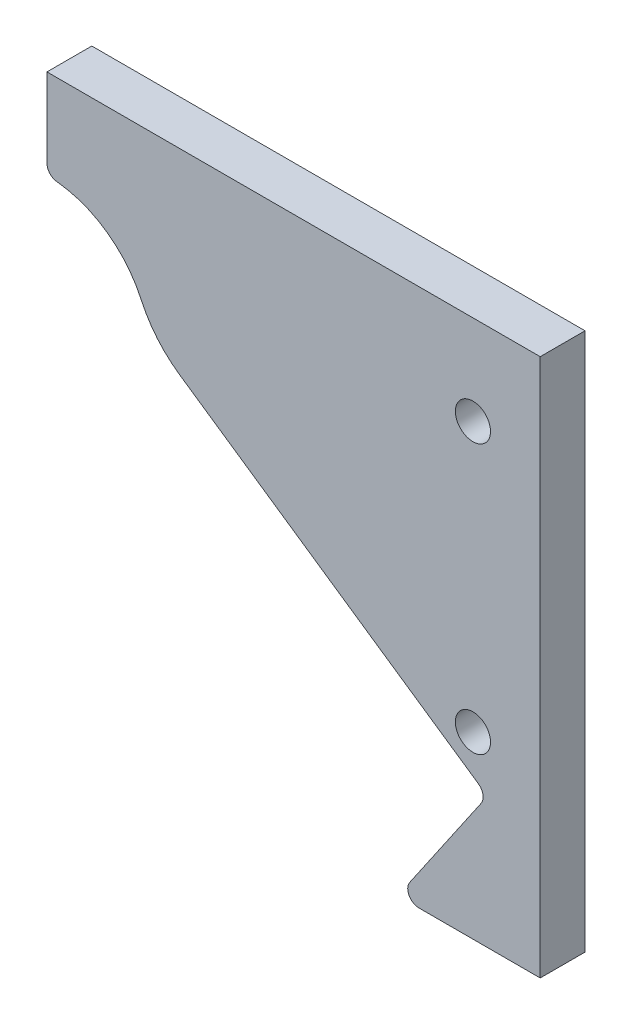
SolidWorks part; units mm, degrees
material "6061 Alloy"
ref_plane "X-Y Datum" through (0, 0, 0) normal (0, 0, 1) x (1, 0, 0)
ref_plane "X-Z Datum" through (0, 0, 0) normal (0, 1, 0) x (1, 0, 0)
ref_plane "Y-Z Datum" through (0, 0, 0) normal (1, 0, 0) x (0, 0, -1)
sketch "Sketch1" plane through (0, 0, 0) normal (0, 0, 1) x (1, 0, 0)
  line L0 (0, 27.3812) -> (69.85, 27.3812)
  line L3 (0, 27.3812) -> (0, 14.6812)
  line L10 (69.85, 27.3812) -> (69.85, -48.8188)
  line L11 (69.85, -48.8188) -> (49.6646, -48.8188)
  line L20 (49.6646, -48.8188) -> (62.3889, -30.2562)
  line L21 (62.3889, -30.2562) -> (18.8122, -0.3851)
  circle A10 centre (60.325, 14.6812) radius 2.4892
  circle A11 centre (60.325, -23.4188) radius 2.4892
  arc A17 (13.3511, 6.1062) -> (0, 14.6812) centre (0, 0) ccw
  arc A18 (18.8122, -0.3851) -> (13.3511, 6.1062) centre (27.7879, 12.7089) cw
  arc A20 (-230.9486, -16.6253) -> (-231.4338, -19.7598) centre (-231.1204, -18.2035) ccw
  point P5 (0, 0)
  point P9 (0, 14.6812)
  point P67 (0, 0)
  point P68 (-1.0707, 0)
  point P69 (0, 0)
  dimension "D1" = 76.2
  dimension "D4" = 49.6646
  dimension "D10" = 4.9784
  dimension "D6" = 15.875
  dimension "D16" = 231.1204
  dimension "D3" = 18.8122
  dimension "D17" = 14.6812
  dimension "D19" = 1.5875
  dimension "D2" = 13.3511
  dimension "D5" = 16.6253
  dimension "D7" = 12.7
  dimension "D9" = 69.85
  dimension "D11" = 25.4
  dimension "D12" = 9.525
  dimension "D13" = 12.7
  dimension "D14" = 9.525
  dimension "D15" = 230.9486
  dimension "D18" = 231.4338
extrude "Boss-Extrude1" add sketch "Sketch1" along normal mid plane 6.35 contours A18 L21 L20 L11 L10 L0 L3 A17 A11 A10
fillet "Fillet1" radius 1.5875 3 edges at (0, 14.6812, 0) (49.6646, -48.8188, 0) (62.3889, -30.2562, 0)
